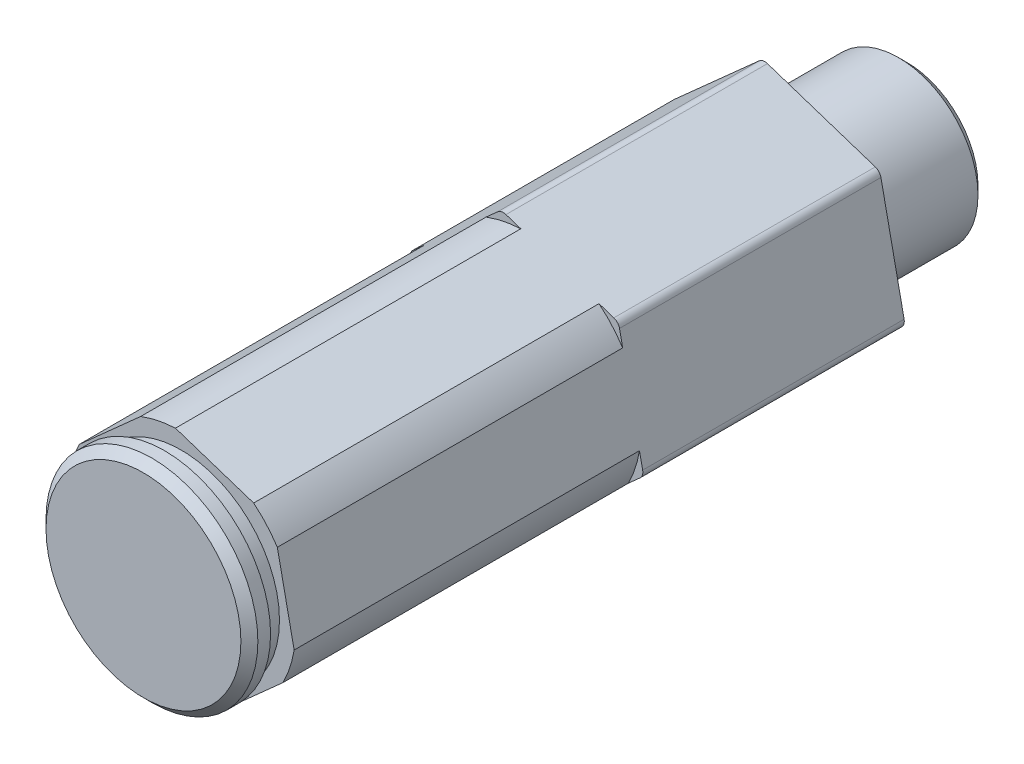
SolidWorks part; units mm, degrees
material "6061-T6 (SS)"
ref_plane "Front Plane" through (0, 0, 0) normal (0, 0, 1) x (1, 0, 0)
ref_plane "Top Plane" through (0, 0, 0) normal (0, 1, 0) x (1, 0, 0)
ref_plane "Right Plane" through (0, 0, 0) normal (1, 0, 0) x (0, 0, -1)
sketch "Sketch2" plane through (0, 0, 0) normal (1, 0, 0) x (0, 0, -1)
  line L0 (-6.4975, 0) -> (22.8854, 0) construction
  line L1 (-22.8854, 6.35) -> (-22.8854, 0)
  line L2 (-22.8854, 0) -> (22.8854, 0)
  line L8 (22.8854, 4.7625) -> (15.748, 4.7625)
  line L9 (15.748, 4.7625) -> (15.748, 6.8623)
  line L10 (15.748, 6.8623) -> (-20.6248, 6.8623)
  line L11 (-20.6248, 6.8623) -> (-20.6248, 5.8928)
  line L12 (-20.6248, 5.8928) -> (-21.6154, 5.8928)
  line L13 (-21.6154, 5.8928) -> (-21.6154, 6.35)
  line L14 (-21.6154, 6.35) -> (-22.8854, 6.35)
  line L15 (22.8854, 4.7625) -> (22.8854, 0)
  point P19 (0, 0)
  dimension "D1" = 0.9906
  dimension "D2" = 36.3728
  dimension "D3" = 7.1374
  dimension "D4" = 1.27
  dimension "D6" = 13.7246
  dimension "D7" = 12.7
  dimension "D8" = 11.7856
  dimension "D9" = 9.525
revolve "Revolve1" add sketch "Sketch2" angle 360 about L0
sketch "Sketch3" plane through (0, 0, 22.8854) normal (0, 0, 1) x (1, 0, 0)
  line L1 (1.5096, -7.2382) -> (7.0233, -2.3117)
  line L2 (7.0233, -2.3117) -> (5.5137, 4.9265)
  line L3 (5.5137, 4.9265) -> (-1.5096, 7.2382)
  line L4 (-1.5096, 7.2382) -> (-7.0233, 2.3117)
  line L5 (-7.0233, 2.3117) -> (-5.5137, -4.9265)
  line L6 (-5.5137, -4.9265) -> (1.5096, -7.2382)
  circle A0 centre (0, 0) radius 6.4033 construction
  dimension "D1" = 12.8067
extrude "Cut-Extrude1" cut sketch "Sketch3" against normal through all flip side to cut
chamfer "Chamfer1" distance 0.508 angle 45 2 edges at (6.35, 0, 22.8854) (4.7625, 0, -22.8854)
sketch "Sketch4" plane through (0, 0, -15.748) normal (0, 0, -1) x (-1, 0, 0)
  line L0 (-4.3458, 5.3109) -> (0.3417, 6.8538) construction
  line L1 (-1.5096, -7.2382) -> (5.5137, -4.9265)
  line L2 (5.5137, -4.9265) -> (7.0233, 2.3117)
  line L3 (7.0233, 2.3117) -> (1.5096, 7.2382)
  line L4 (1.5096, 7.2382) -> (-5.5137, 4.9265)
  line L5 (-5.5137, 4.9265) -> (-7.0233, -2.3117)
  line L6 (-7.0233, -2.3117) -> (-1.5096, -7.2382)
  line L10 (0.3417, 6.8538) -> (-4.3458, 5.3109) construction
  circle A0 centre (0, 0) radius 6.4033 construction
extrude "Boss-Extrude1" add sketch "Sketch4" against normal offset from surface (15.6718 mm away) 20.701 up to face at (5.8928, 0, 20.6248)
fillet "Fillet1" radius 0.508 6 edges at (1.5096, -7.2382, -7.9121) (-1.5096, 7.2382, -7.9121) (-7.0233, 2.3117, -7.9121) (-5.5137, -4.9265, -7.9121) (7.0233, -2.3117, -7.9121) (5.5137, 4.9265, -7.9121)
